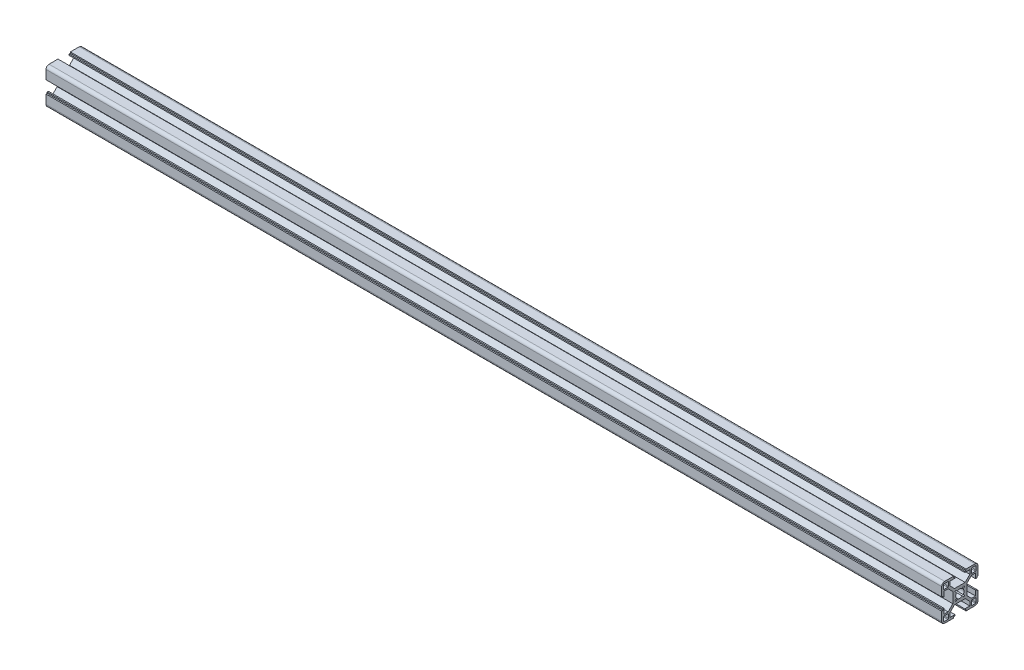
SolidWorks part; units mm, degrees
ref_plane "前视基准面" through (0, 0, 0) normal (0, 0, 1) x (1, 0, 0)
ref_plane "上视基准面" through (0, 0, 0) normal (0, 1, 0) x (1, 0, 0)
ref_plane "右视基准面" through (0, 0, 0) normal (1, 0, 0) x (0, 0, -1)
other "Configuration Table"
sketch "草图1" plane through (0, 0, 0) normal (1, 0, 0) x (0, 0, -1)
  line L0 (-5.1496, -13.7047) -> (-4.1496, -13.7047)
  line L1 (-4.1496, -13.7047) -> (-4.1496, -12.7047)
  line L2 (-4.1496, -12.7047) -> (-8.2996, -12.7047)
  line L3 (-8.2996, -12.7047) -> (-8.2996, -9.3689)
  line L4 (-8.2996, -9.3689) -> (-4.4354, -5.5047)
  line L5 (-4.4354, -5.5047) -> (4.3362, -5.5047)
  line L6 (4.3362, -5.5047) -> (8.2004, -9.3689)
  line L7 (8.2004, -9.3689) -> (8.2004, -12.7047)
  line L8 (8.2004, -12.7047) -> (4.0504, -12.7047)
  line L9 (4.0504, -12.7047) -> (4.0504, -13.7047)
  line L10 (4.0504, -13.7047) -> (5.0504, -13.7047)
  line L11 (5.0504, -13.7047) -> (5.0504, -14.7047)
  line L12 (5.0504, -14.7047) -> (12.4504, -14.7047)
  line L13 (14.9504, -12.2047) -> (14.9504, -4.8047)
  line L14 (14.9504, -4.8047) -> (13.9504, -4.8047)
  line L15 (13.9504, -4.8047) -> (13.9504, -3.8047)
  line L16 (13.9504, -3.8047) -> (12.9504, -3.8047)
  line L17 (12.9504, -3.8047) -> (12.9504, -7.9547)
  line L18 (12.9504, -7.9547) -> (9.6146, -7.9547)
  line L19 (9.6146, -7.9547) -> (5.7504, -4.0905)
  line L20 (5.7504, -4.0905) -> (5.7504, 4.6811)
  line L21 (5.7504, 4.6811) -> (9.6146, 8.5453)
  line L22 (9.6146, 8.5453) -> (12.9504, 8.5453)
  line L23 (12.9504, 8.5453) -> (12.9504, 4.3953)
  line L24 (12.9504, 4.3953) -> (13.9504, 4.3953)
  line L25 (13.9504, 4.3953) -> (13.9504, 5.3953)
  line L26 (13.9504, 5.3953) -> (14.9504, 5.3953)
  line L27 (14.9504, 5.3953) -> (14.9504, 12.7953)
  line L28 (12.4504, 15.2953) -> (5.0504, 15.2953)
  line L29 (5.0504, 15.2953) -> (5.0504, 14.2953)
  line L30 (5.0504, 14.2953) -> (4.0504, 14.2953)
  line L31 (4.0504, 14.2953) -> (4.0504, 13.2953)
  line L32 (4.0504, 13.2953) -> (8.2004, 13.2953)
  line L33 (8.2004, 13.2953) -> (8.2004, 9.9595)
  line L34 (8.2004, 9.9595) -> (4.3362, 6.0953)
  line L35 (4.3362, 6.0953) -> (-4.4354, 6.0953)
  line L36 (-4.4354, 6.0953) -> (-8.2996, 9.9595)
  line L37 (-8.2996, 9.9595) -> (-8.2996, 13.2953)
  line L38 (-8.2996, 13.2953) -> (-4.1496, 13.2953)
  line L39 (-4.1496, 13.2953) -> (-4.1496, 14.2953)
  line L40 (-4.1496, 14.2953) -> (-5.1496, 14.2953)
  line L41 (-5.1496, 14.2953) -> (-5.1496, 15.2953)
  line L42 (-5.1496, 15.2953) -> (-12.5496, 15.2953)
  line L43 (-15.0496, 12.7953) -> (-15.0496, 5.3953)
  line L44 (-15.0496, 5.3953) -> (-14.0496, 5.3953)
  line L45 (-14.0496, 5.3953) -> (-14.0496, 4.3953)
  line L46 (-14.0496, 4.3953) -> (-13.0496, 4.3953)
  line L47 (-13.0496, 4.3953) -> (-13.0496, 8.5453)
  line L48 (-13.0496, 8.5453) -> (-9.7138, 8.5453)
  line L49 (-9.7138, 8.5453) -> (-5.8496, 4.6811)
  line L50 (-5.8496, 4.6811) -> (-5.8496, -4.0905)
  line L51 (-5.8496, -4.0905) -> (-9.7138, -7.9547)
  line L52 (-9.7138, -7.9547) -> (-13.0496, -7.9547)
  line L53 (-13.0496, -7.9547) -> (-13.0496, -3.8047)
  line L54 (-13.0496, -3.8047) -> (-14.0496, -3.8047)
  line L55 (-14.0496, -3.8047) -> (-14.0496, -4.8047)
  line L56 (-14.0496, -4.8047) -> (-15.0496, -4.8047)
  line L57 (-15.0496, -4.8047) -> (-15.0496, -12.2047)
  line L58 (-12.5496, -14.7047) -> (-5.1496, -14.7047)
  line L59 (-5.1496, -14.7047) -> (-5.1496, -13.7047)
  line L60 (-10.0496, 9.7953) -> (-13.0496, 9.7953)
  line L61 (-13.5496, 10.2953) -> (-13.5496, 13.2953)
  line L62 (-13.0496, 13.7953) -> (-10.0496, 13.7953)
  line L63 (-9.5496, 13.2953) -> (-9.5496, 10.2953)
  line L64 (-10.0496, -13.2047) -> (-13.0496, -13.2047)
  line L65 (-13.5496, -12.7047) -> (-13.5496, -9.7047)
  line L66 (-13.0496, -9.2047) -> (-10.0496, -9.2047)
  line L67 (-9.5496, -9.7047) -> (-9.5496, -12.7047)
  line L68 (12.9504, 9.7953) -> (9.9504, 9.7953)
  line L69 (9.4504, 10.2953) -> (9.4504, 13.2953)
  line L70 (9.9504, 13.7953) -> (12.9504, 13.7953)
  line L71 (13.4504, 13.2953) -> (13.4504, 10.2953)
  line L72 (13.4504, -9.7047) -> (13.4504, -12.7047)
  line L73 (12.9504, -13.2047) -> (9.9504, -13.2047)
  line L74 (9.4504, -12.7047) -> (9.4504, -9.7047)
  line L75 (9.9504, -9.2047) -> (12.9504, -9.2047)
  line L76 (-4.08, 3.6186) -> (-3.3729, 4.3257)
  line L77 (-3.3729, 4.3257) -> (-2.074, 3.0269)
  line L78 (1.9749, 3.0269) -> (3.2737, 4.3257)
  line L79 (3.2737, 4.3257) -> (3.9808, 3.6186)
  line L80 (3.9808, 3.6186) -> (2.682, 2.3198)
  line L81 (2.682, -1.7291) -> (3.9808, -3.028)
  line L82 (3.9808, -3.028) -> (3.2737, -3.7351)
  line L83 (3.2737, -3.7351) -> (1.9749, -2.4362)
  line L84 (-2.074, -2.4362) -> (-3.3729, -3.7351)
  line L85 (-3.3729, -3.7351) -> (-4.08, -3.028)
  line L86 (-4.08, -3.028) -> (-2.7811, -1.7291)
  line L87 (-2.7811, 2.3198) -> (-4.08, 3.6186)
  arc A0 (12.4504, -14.7047) -> (14.9504, -12.2047) centre (12.4504, -12.2047) ccw
  arc A1 (14.9504, 12.7953) -> (12.4504, 15.2953) centre (12.4504, 12.7953) ccw
  arc A2 (-12.5496, 15.2953) -> (-15.0496, 12.7953) centre (-12.5496, 12.7953) ccw
  arc A3 (-15.0496, -12.2047) -> (-12.5496, -14.7047) centre (-12.5496, -12.2047) ccw
  arc A4 (-9.5496, 10.2953) -> (-10.0496, 9.7953) centre (-10.0496, 10.2953) cw
  arc A5 (-13.0496, 9.7953) -> (-13.5496, 10.2953) centre (-13.0496, 10.2953) cw
  arc A6 (-13.5496, 13.2953) -> (-13.0496, 13.7953) centre (-13.0496, 13.2953) cw
  arc A7 (-10.0496, 13.7953) -> (-9.5496, 13.2953) centre (-10.0496, 13.2953) cw
  arc A8 (-9.5496, -12.7047) -> (-10.0496, -13.2047) centre (-10.0496, -12.7047) cw
  arc A9 (-13.0496, -13.2047) -> (-13.5496, -12.7047) centre (-13.0496, -12.7047) cw
  arc A10 (-13.5496, -9.7047) -> (-13.0496, -9.2047) centre (-13.0496, -9.7047) cw
  arc A11 (-10.0496, -9.2047) -> (-9.5496, -9.7047) centre (-10.0496, -9.7047) cw
  arc A12 (13.4504, 10.2953) -> (12.9504, 9.7953) centre (12.9504, 10.2953) cw
  arc A13 (9.9504, 9.7953) -> (9.4504, 10.2953) centre (9.9504, 10.2953) cw
  arc A14 (9.4504, 13.2953) -> (9.9504, 13.7953) centre (9.9504, 13.2953) cw
  arc A15 (12.9504, 13.7953) -> (13.4504, 13.2953) centre (12.9504, 13.2953) cw
  arc A16 (12.9504, -9.2047) -> (13.4504, -9.7047) centre (12.9504, -9.7047) cw
  arc A17 (13.4504, -12.7047) -> (12.9504, -13.2047) centre (12.9504, -12.7047) cw
  arc A18 (9.9504, -13.2047) -> (9.4504, -12.7047) centre (9.9504, -12.7047) cw
  arc A19 (9.4504, -9.7047) -> (9.9504, -9.2047) centre (9.9504, -9.7047) cw
  arc A20 (-2.074, 3.0269) -> (1.9749, 3.0269) centre (-0.0496, 0.2953) cw
  arc A21 (2.682, 2.3198) -> (2.682, -1.7291) centre (-0.0496, 0.2953) cw
  arc A22 (1.9749, -2.4362) -> (-2.074, -2.4362) centre (-0.0496, 0.2953) cw
  arc A23 (-2.7811, -1.7291) -> (-2.7811, 2.3198) centre (-0.0496, 0.2953) cw
extrude "凸台-拉伸1" add sketch "草图1" against normal blind 50
sketch "草图2" plane through (0, 0, 0) normal (1, 0, 0) x (0, 0, -1)
  line L4 (-13.0496, 9.7953) -> (-10.0496, 9.7953)
  line L5 (-13.5496, 13.2953) -> (-13.5496, 10.2953)
  line L6 (-10.0496, 13.7953) -> (-13.0496, 13.7953)
  line L7 (-9.5496, 10.2953) -> (-9.5496, 13.2953)
  line L8 (-13.0496, 9.7953) -> (-10.0496, 9.7953)
  line L9 (-13.5496, 13.2953) -> (-13.5496, 10.2953)
  line L10 (-10.0496, 13.7953) -> (-13.0496, 13.7953)
  line L11 (-9.5496, 10.2953) -> (-9.5496, 13.2953)
  line L12 (-13.0496, -13.2047) -> (-10.0496, -13.2047)
  line L13 (-13.5496, -9.7047) -> (-13.5496, -12.7047)
  line L14 (-10.0496, -9.2047) -> (-13.0496, -9.2047)
  line L15 (-9.5496, -12.7047) -> (-9.5496, -9.7047)
  line L16 (-13.0496, -13.2047) -> (-10.0496, -13.2047)
  line L17 (-13.5496, -9.7047) -> (-13.5496, -12.7047)
  line L18 (-10.0496, -9.2047) -> (-13.0496, -9.2047)
  line L19 (-9.5496, -12.7047) -> (-9.5496, -9.7047)
  line L20 (9.4504, 13.2953) -> (9.4504, 10.2953)
  line L21 (12.9504, 13.7953) -> (9.9504, 13.7953)
  line L22 (13.4504, 10.2953) -> (13.4504, 13.2953)
  line L23 (9.9504, 9.7953) -> (12.9504, 9.7953)
  line L24 (9.4504, 13.2953) -> (9.4504, 10.2953)
  line L25 (12.9504, 13.7953) -> (9.9504, 13.7953)
  line L26 (13.4504, 10.2953) -> (13.4504, 13.2953)
  line L27 (9.9504, 9.7953) -> (12.9504, 9.7953)
  line L28 (9.4504, -9.7047) -> (9.4504, -12.7047)
  line L29 (12.9504, -9.2047) -> (9.9504, -9.2047)
  line L30 (13.4504, -12.7047) -> (13.4504, -9.7047)
  line L31 (9.9504, -13.2047) -> (12.9504, -13.2047)
  line L32 (9.4504, -9.7047) -> (9.4504, -12.7047)
  line L33 (12.9504, -9.2047) -> (9.9504, -9.2047)
  line L34 (13.4504, -12.7047) -> (13.4504, -9.7047)
  line L35 (9.9504, -13.2047) -> (12.9504, -13.2047)
  line L44 (-3.3729, -3.7351) -> (-2.074, -2.4362)
  line L45 (-4.08, -3.028) -> (-3.3729, -3.7351)
  line L46 (-2.7811, -1.7291) -> (-4.08, -3.028)
  line L47 (-4.08, 3.6186) -> (-2.7811, 2.3198)
  line L48 (-3.3729, 4.3257) -> (-4.08, 3.6186)
  line L49 (-2.074, 3.0269) -> (-3.3729, 4.3257)
  line L50 (3.2737, 4.3257) -> (1.9749, 3.0269)
  line L51 (3.9808, 3.6186) -> (3.2737, 4.3257)
  line L52 (2.682, 2.3198) -> (3.9808, 3.6186)
  line L53 (3.9808, -3.028) -> (2.682, -1.7291)
  line L54 (3.2737, -3.7351) -> (3.9808, -3.028)
  line L55 (1.9749, -2.4362) -> (3.2737, -3.7351)
  line L56 (-3.3729, -3.7351) -> (-2.074, -2.4362)
  line L57 (-4.08, -3.028) -> (-3.3729, -3.7351)
  line L58 (-2.7811, -1.7291) -> (-4.08, -3.028)
  line L59 (-4.08, 3.6186) -> (-2.7811, 2.3198)
  line L60 (-3.3729, 4.3257) -> (-4.08, 3.6186)
  line L61 (-2.074, 3.0269) -> (-3.3729, 4.3257)
  line L62 (3.2737, 4.3257) -> (1.9749, 3.0269)
  line L63 (3.9808, 3.6186) -> (3.2737, 4.3257)
  line L64 (2.682, 2.3198) -> (3.9808, 3.6186)
  line L65 (3.9808, -3.028) -> (2.682, -1.7291)
  line L66 (3.2737, -3.7351) -> (3.9808, -3.028)
  line L67 (1.9749, -2.4362) -> (3.2737, -3.7351)
  line L68 (-15.0496, -4.8047) -> (-15.0496, -12.2047)
  line L69 (-14.0496, -4.8047) -> (-15.0496, -4.8047)
  line L70 (-14.0496, -3.8047) -> (-14.0496, -4.8047)
  line L71 (-13.0496, -3.8047) -> (-14.0496, -3.8047)
  line L72 (-13.0496, -7.9547) -> (-13.0496, -3.8047)
  line L73 (-9.7138, -7.9547) -> (-13.0496, -7.9547)
  line L74 (-5.8496, -4.0905) -> (-9.7138, -7.9547)
  line L75 (-5.8496, 4.6811) -> (-5.8496, -4.0905)
  line L76 (-9.7138, 8.5453) -> (-5.8496, 4.6811)
  line L77 (-13.0496, 8.5453) -> (-9.7138, 8.5453)
  line L78 (-13.0496, 4.3953) -> (-13.0496, 8.5453)
  line L79 (-14.0496, 4.3953) -> (-13.0496, 4.3953)
  line L80 (-14.0496, 5.3953) -> (-14.0496, 4.3953)
  line L81 (-15.0496, 5.3953) -> (-14.0496, 5.3953)
  line L82 (-15.0496, 12.7953) -> (-15.0496, 5.3953)
  line L83 (-5.1496, 15.2953) -> (-12.5496, 15.2953)
  line L84 (-5.1496, 14.2953) -> (-5.1496, 15.2953)
  line L85 (-4.1496, 14.2953) -> (-5.1496, 14.2953)
  line L86 (-4.1496, 13.2953) -> (-4.1496, 14.2953)
  line L87 (-8.2996, 13.2953) -> (-4.1496, 13.2953)
  line L88 (-8.2996, 9.9595) -> (-8.2996, 13.2953)
  line L89 (-4.4354, 6.0953) -> (-8.2996, 9.9595)
  line L90 (4.3362, 6.0953) -> (-4.4354, 6.0953)
  line L91 (8.2004, 9.9595) -> (4.3362, 6.0953)
  line L92 (8.2004, 13.2953) -> (8.2004, 9.9595)
  line L93 (4.0504, 13.2953) -> (8.2004, 13.2953)
  line L94 (4.0504, 14.2953) -> (4.0504, 13.2953)
  line L95 (5.0504, 14.2953) -> (4.0504, 14.2953)
  line L96 (5.0504, 15.2953) -> (5.0504, 14.2953)
  line L97 (12.4504, 15.2953) -> (5.0504, 15.2953)
  line L98 (14.9504, 5.3953) -> (14.9504, 12.7953)
  line L99 (13.9504, 5.3953) -> (14.9504, 5.3953)
  line L100 (13.9504, 4.3953) -> (13.9504, 5.3953)
  line L101 (12.9504, 4.3953) -> (13.9504, 4.3953)
  line L102 (12.9504, 8.5453) -> (12.9504, 4.3953)
  line L103 (9.6146, 8.5453) -> (12.9504, 8.5453)
  line L104 (5.7504, 4.6811) -> (9.6146, 8.5453)
  line L105 (5.7504, -4.0905) -> (5.7504, 4.6811)
  line L106 (9.6146, -7.9547) -> (5.7504, -4.0905)
  line L107 (12.9504, -7.9547) -> (9.6146, -7.9547)
  line L108 (12.9504, -3.8047) -> (12.9504, -7.9547)
  line L109 (13.9504, -3.8047) -> (12.9504, -3.8047)
  line L110 (13.9504, -4.8047) -> (13.9504, -3.8047)
  line L111 (14.9504, -4.8047) -> (13.9504, -4.8047)
  line L112 (14.9504, -12.2047) -> (14.9504, -4.8047)
  line L113 (5.0504, -14.7047) -> (12.4504, -14.7047)
  line L114 (5.0504, -13.7047) -> (5.0504, -14.7047)
  line L115 (4.0504, -13.7047) -> (5.0504, -13.7047)
  line L116 (4.0504, -12.7047) -> (4.0504, -13.7047)
  line L117 (8.2004, -12.7047) -> (4.0504, -12.7047)
  line L118 (8.2004, -9.3689) -> (8.2004, -12.7047)
  line L119 (4.3362, -5.5047) -> (8.2004, -9.3689)
  line L120 (-4.4354, -5.5047) -> (4.3362, -5.5047)
  line L121 (-8.2996, -9.3689) -> (-4.4354, -5.5047)
  line L122 (-8.2996, -12.7047) -> (-8.2996, -9.3689)
  line L123 (-4.1496, -12.7047) -> (-8.2996, -12.7047)
  line L124 (-4.1496, -13.7047) -> (-4.1496, -12.7047)
  line L125 (-5.1496, -13.7047) -> (-4.1496, -13.7047)
  line L126 (-5.1496, -14.7047) -> (-5.1496, -13.7047)
  line L127 (-12.5496, -14.7047) -> (-5.1496, -14.7047)
  line L128 (-15.0496, -4.8047) -> (-15.0496, -12.2047)
  line L129 (-14.0496, -4.8047) -> (-15.0496, -4.8047)
  line L130 (-14.0496, -3.8047) -> (-14.0496, -4.8047)
  line L131 (-13.0496, -3.8047) -> (-14.0496, -3.8047)
  line L132 (-13.0496, -7.9547) -> (-13.0496, -3.8047)
  line L133 (-9.7138, -7.9547) -> (-13.0496, -7.9547)
  line L134 (-5.8496, -4.0905) -> (-9.7138, -7.9547)
  line L135 (-5.8496, 4.6811) -> (-5.8496, -4.0905)
  line L136 (-9.7138, 8.5453) -> (-5.8496, 4.6811)
  line L137 (-13.0496, 8.5453) -> (-9.7138, 8.5453)
  line L138 (-13.0496, 4.3953) -> (-13.0496, 8.5453)
  line L139 (-14.0496, 4.3953) -> (-13.0496, 4.3953)
  line L140 (-14.0496, 5.3953) -> (-14.0496, 4.3953)
  line L141 (-15.0496, 5.3953) -> (-14.0496, 5.3953)
  line L142 (-15.0496, 12.7953) -> (-15.0496, 5.3953)
  line L143 (-5.1496, 15.2953) -> (-12.5496, 15.2953)
  line L144 (-5.1496, 14.2953) -> (-5.1496, 15.2953)
  line L145 (-4.1496, 14.2953) -> (-5.1496, 14.2953)
  line L146 (-4.1496, 13.2953) -> (-4.1496, 14.2953)
  line L147 (-8.2996, 13.2953) -> (-4.1496, 13.2953)
  line L148 (-8.2996, 9.9595) -> (-8.2996, 13.2953)
  line L149 (-4.4354, 6.0953) -> (-8.2996, 9.9595)
  line L150 (4.3362, 6.0953) -> (-4.4354, 6.0953)
  line L151 (8.2004, 9.9595) -> (4.3362, 6.0953)
  line L152 (8.2004, 13.2953) -> (8.2004, 9.9595)
  line L153 (4.0504, 13.2953) -> (8.2004, 13.2953)
  line L154 (4.0504, 14.2953) -> (4.0504, 13.2953)
  line L155 (5.0504, 14.2953) -> (4.0504, 14.2953)
  line L156 (5.0504, 15.2953) -> (5.0504, 14.2953)
  line L157 (12.4504, 15.2953) -> (5.0504, 15.2953)
  line L158 (14.9504, 5.3953) -> (14.9504, 12.7953)
  line L159 (13.9504, 5.3953) -> (14.9504, 5.3953)
  line L160 (13.9504, 4.3953) -> (13.9504, 5.3953)
  line L161 (12.9504, 4.3953) -> (13.9504, 4.3953)
  line L162 (12.9504, 8.5453) -> (12.9504, 4.3953)
  line L163 (9.6146, 8.5453) -> (12.9504, 8.5453)
  line L164 (5.7504, 4.6811) -> (9.6146, 8.5453)
  line L165 (5.7504, -4.0905) -> (5.7504, 4.6811)
  line L166 (9.6146, -7.9547) -> (5.7504, -4.0905)
  line L167 (12.9504, -7.9547) -> (9.6146, -7.9547)
  line L168 (12.9504, -3.8047) -> (12.9504, -7.9547)
  line L169 (13.9504, -3.8047) -> (12.9504, -3.8047)
  line L170 (13.9504, -4.8047) -> (13.9504, -3.8047)
  line L171 (14.9504, -4.8047) -> (13.9504, -4.8047)
  line L172 (14.9504, -12.2047) -> (14.9504, -4.8047)
  line L173 (5.0504, -14.7047) -> (12.4504, -14.7047)
  line L174 (5.0504, -13.7047) -> (5.0504, -14.7047)
  line L175 (4.0504, -13.7047) -> (5.0504, -13.7047)
  line L176 (4.0504, -12.7047) -> (4.0504, -13.7047)
  line L177 (8.2004, -12.7047) -> (4.0504, -12.7047)
  line L178 (8.2004, -9.3689) -> (8.2004, -12.7047)
  line L179 (4.3362, -5.5047) -> (8.2004, -9.3689)
  line L180 (-4.4354, -5.5047) -> (4.3362, -5.5047)
  line L181 (-8.2996, -9.3689) -> (-4.4354, -5.5047)
  line L182 (-8.2996, -12.7047) -> (-8.2996, -9.3689)
  line L183 (-4.1496, -12.7047) -> (-8.2996, -12.7047)
  line L184 (-4.1496, -13.7047) -> (-4.1496, -12.7047)
  line L185 (-5.1496, -13.7047) -> (-4.1496, -13.7047)
  line L186 (-5.1496, -14.7047) -> (-5.1496, -13.7047)
  line L187 (-12.5496, -14.7047) -> (-5.1496, -14.7047)
  arc A4 (-13.5496, 10.2953) -> (-13.0496, 9.7953) centre (-13.0496, 10.2953) ccw
  arc A5 (-13.0496, 13.7953) -> (-13.5496, 13.2953) centre (-13.0496, 13.2953) ccw
  arc A6 (-9.5496, 13.2953) -> (-10.0496, 13.7953) centre (-10.0496, 13.2953) ccw
  arc A7 (-10.0496, 9.7953) -> (-9.5496, 10.2953) centre (-10.0496, 10.2953) ccw
  arc A8 (-13.5496, 10.2953) -> (-13.0496, 9.7953) centre (-13.0496, 10.2953) ccw
  arc A9 (-13.0496, 13.7953) -> (-13.5496, 13.2953) centre (-13.0496, 13.2953) ccw
  arc A10 (-9.5496, 13.2953) -> (-10.0496, 13.7953) centre (-10.0496, 13.2953) ccw
  arc A11 (-10.0496, 9.7953) -> (-9.5496, 10.2953) centre (-10.0496, 10.2953) ccw
  arc A12 (-12.5496, 15.2953) -> (-15.0496, 12.7953) centre (-12.5496, 12.7953) ccw
  arc A13 (14.9504, 12.7953) -> (12.4504, 15.2953) centre (12.4504, 12.7953) ccw
  arc A14 (12.4504, -14.7047) -> (14.9504, -12.2047) centre (12.4504, -12.2047) ccw
  arc A15 (-15.0496, -12.2047) -> (-12.5496, -14.7047) centre (-12.5496, -12.2047) ccw
  arc A16 (-12.5496, 15.2953) -> (-15.0496, 12.7953) centre (-12.5496, 12.7953) ccw
  arc A17 (14.9504, 12.7953) -> (12.4504, 15.2953) centre (12.4504, 12.7953) ccw
  arc A18 (12.4504, -14.7047) -> (14.9504, -12.2047) centre (12.4504, -12.2047) ccw
  arc A19 (-15.0496, -12.2047) -> (-12.5496, -14.7047) centre (-12.5496, -12.2047) ccw
  arc A20 (-13.5496, -12.7047) -> (-13.0496, -13.2047) centre (-13.0496, -12.7047) ccw
  arc A21 (-13.0496, -9.2047) -> (-13.5496, -9.7047) centre (-13.0496, -9.7047) ccw
  arc A22 (-9.5496, -9.7047) -> (-10.0496, -9.2047) centre (-10.0496, -9.7047) ccw
  arc A23 (-10.0496, -13.2047) -> (-9.5496, -12.7047) centre (-10.0496, -12.7047) ccw
  arc A24 (-13.5496, -12.7047) -> (-13.0496, -13.2047) centre (-13.0496, -12.7047) ccw
  arc A25 (-13.0496, -9.2047) -> (-13.5496, -9.7047) centre (-13.0496, -9.7047) ccw
  arc A26 (-9.5496, -9.7047) -> (-10.0496, -9.2047) centre (-10.0496, -9.7047) ccw
  arc A27 (-10.0496, -13.2047) -> (-9.5496, -12.7047) centre (-10.0496, -12.7047) ccw
  arc A28 (9.9504, 13.7953) -> (9.4504, 13.2953) centre (9.9504, 13.2953) ccw
  arc A29 (13.4504, 13.2953) -> (12.9504, 13.7953) centre (12.9504, 13.2953) ccw
  arc A30 (12.9504, 9.7953) -> (13.4504, 10.2953) centre (12.9504, 10.2953) ccw
  arc A31 (9.4504, 10.2953) -> (9.9504, 9.7953) centre (9.9504, 10.2953) ccw
  arc A32 (9.9504, 13.7953) -> (9.4504, 13.2953) centre (9.9504, 13.2953) ccw
  arc A33 (13.4504, 13.2953) -> (12.9504, 13.7953) centre (12.9504, 13.2953) ccw
  arc A34 (12.9504, 9.7953) -> (13.4504, 10.2953) centre (12.9504, 10.2953) ccw
  arc A35 (9.4504, 10.2953) -> (9.9504, 9.7953) centre (9.9504, 10.2953) ccw
  arc A36 (9.9504, -9.2047) -> (9.4504, -9.7047) centre (9.9504, -9.7047) ccw
  arc A37 (13.4504, -9.7047) -> (12.9504, -9.2047) centre (12.9504, -9.7047) ccw
  arc A38 (12.9504, -13.2047) -> (13.4504, -12.7047) centre (12.9504, -12.7047) ccw
  arc A39 (9.4504, -12.7047) -> (9.9504, -13.2047) centre (9.9504, -12.7047) ccw
  arc A40 (9.9504, -9.2047) -> (9.4504, -9.7047) centre (9.9504, -9.7047) ccw
  arc A41 (13.4504, -9.7047) -> (12.9504, -9.2047) centre (12.9504, -9.7047) ccw
  arc A42 (12.9504, -13.2047) -> (13.4504, -12.7047) centre (12.9504, -12.7047) ccw
  arc A43 (9.4504, -12.7047) -> (9.9504, -13.2047) centre (9.9504, -12.7047) ccw
  arc A44 (-2.7811, 2.3198) -> (-2.7811, -1.7291) centre (-0.0496, 0.2953) ccw
  arc A45 (1.9749, 3.0269) -> (-2.074, 3.0269) centre (-0.0496, 0.2953) ccw
  arc A46 (2.682, -1.7291) -> (2.682, 2.3198) centre (-0.0496, 0.2953) ccw
  arc A47 (-2.074, -2.4362) -> (1.9749, -2.4362) centre (-0.0496, 0.2953) ccw
  arc A48 (-2.7811, 2.3198) -> (-2.7811, -1.7291) centre (-0.0496, 0.2953) ccw
  arc A49 (1.9749, 3.0269) -> (-2.074, 3.0269) centre (-0.0496, 0.2953) ccw
  arc A50 (2.682, -1.7291) -> (2.682, 2.3198) centre (-0.0496, 0.2953) ccw
  arc A51 (-2.074, -2.4362) -> (1.9749, -2.4362) centre (-0.0496, 0.2953) ccw
  dimension "D1" = 0
  dimension "D2" = 0
  dimension "D3" = 0
  dimension "D4" = 0
  dimension "D5" = 0
  dimension "D6" = 0
extrude "凸台-拉伸2" add sketch "草图2" against normal blind 740
